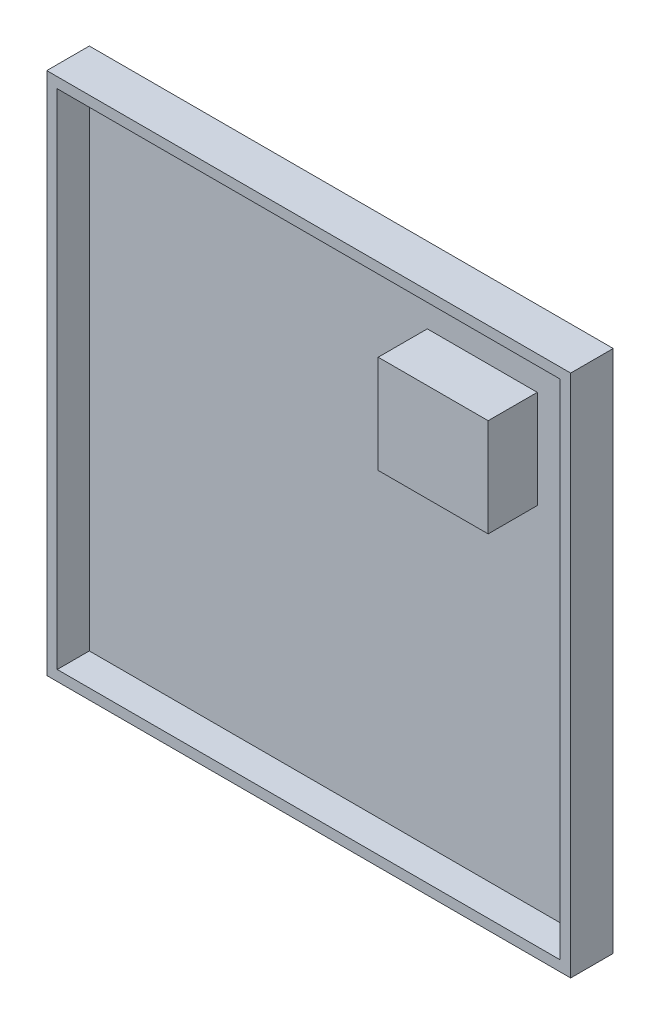
SolidWorks part; units mm, degrees
ref_plane "Front Plane" through (0, 0, 0) normal (0, 0, 1) x (1, 0, 0)
ref_plane "Top Plane" through (0, 0, 0) normal (0, 1, 0) x (1, 0, 0)
ref_plane "Right Plane" through (0, 0, 0) normal (1, 0, 0) x (0, 0, -1)
sketch "Sketch1" plane through (0, 0, 0) normal (0, 0, 1) x (1, 0, 0)
  line L1 (-50.8, -50.8) -> (50.8, -50.8)
  line L2 (-50.8, -50.8) -> (-50.8, 50.8)
  line L3 (-50.8, 50.8) -> (50.8, 50.8)
  line L4 (50.8, -50.8) -> (50.8, 50.8)
  line L5 (-50.8, -50.8) -> (50.8, 50.8) construction
  line L6 (-50.8, 50.8) -> (50.8, -50.8) construction
  point P0 (0, 0)
  dimension "D1" = 101.6
  dimension "D2" = 101.6
extrude "Boss-Extrude1" add sketch "Sketch1" along normal blind 8.255
sketch "Sketch3" plane through (0, 0, 8.255) normal (0, 0, 1) x (1, 0, 0)
  line L0 (50.8, -50.8) -> (50.8, 50.8) construction
  line L1 (-48.768, -48.768) -> (48.768, -48.768)
  line L2 (-48.768, -48.768) -> (-48.768, 48.768)
  line L3 (-48.768, 48.768) -> (48.768, 48.768)
  line L4 (48.768, -48.768) -> (48.768, 48.768)
  line L5 (-48.768, -48.768) -> (48.768, 48.768) construction
  line L6 (-48.768, 48.768) -> (48.768, -48.768) construction
  line L7 (50.8, 50.8) -> (-50.8, 50.8) construction
  point P0 (0, 0)
  dimension "D1" = 2.032
  dimension "D2" = 2.032
extrude "Cut-Extrude1" cut sketch "Sketch3" against normal offset from surface (6.223 mm away) 2.032 up to face at (0, 0, 0)
sketch "Sketch4" plane through (0, 0, 2.032) normal (0, 0, 1) x (1, 0, 0)
  line L0 (50.8, -50.8) -> (50.8, 50.8) construction
  line L1 (16.7786, 19.0836) -> (38.1, 19.0836)
  line L2 (16.7786, 19.0836) -> (16.7786, 38.1)
  line L3 (16.7786, 38.1) -> (38.1, 38.1)
  line L4 (38.1, 19.0836) -> (38.1, 38.1)
  line L5 (16.7786, 19.0836) -> (38.1, 38.1) construction
  line L6 (16.7786, 38.1) -> (38.1, 19.0836) construction
  line L7 (50.8, 50.8) -> (-50.8, 50.8) construction
  point P0 (27.4393, 28.5918)
  dimension "D1" = 12.7
  dimension "D2" = 12.7
extrude "Boss-Extrude2" add sketch "Sketch4" along normal blind 9.525
sketch "Sketch6" plane through (0, 0, 0) normal (0, 0, -1) x (-1, 0, 0)
  line L0 (-18.8106, 21.1156) -> (-36.068, 21.1156)
  line L1 (-18.8106, 21.1156) -> (-18.8106, 36.068)
  line L2 (-36.068, 21.1156) -> (-36.068, 36.068)
  line L3 (-18.8106, 36.068) -> (-36.068, 36.068)
  line L4 (-18.8106, 21.1156) -> (-36.068, 36.068) construction
  line L5 (-36.068, 21.1156) -> (-18.8106, 36.068) construction
  line L6 (-38.1, 38.1) -> (-16.7786, 38.1) construction
  line L7 (-38.1, 19.0836) -> (-38.1, 38.1) construction
  line L8 (-16.7786, 38.1) -> (-16.7786, 19.0836) construction
  line L9 (-16.7786, 19.0836) -> (-38.1, 19.0836) construction
  point P1 (-27.4393, 28.5918)
  dimension "D1" = 2.032
  dimension "D2" = 2.032
  dimension "D3" = 2.032
  dimension "D4" = 2.032
extrude "Cut-Extrude2" cut sketch "Sketch6" against normal offset from surface (9.525 mm away) 2.032 up to face at (27.4393, 28.5918, 11.557)
